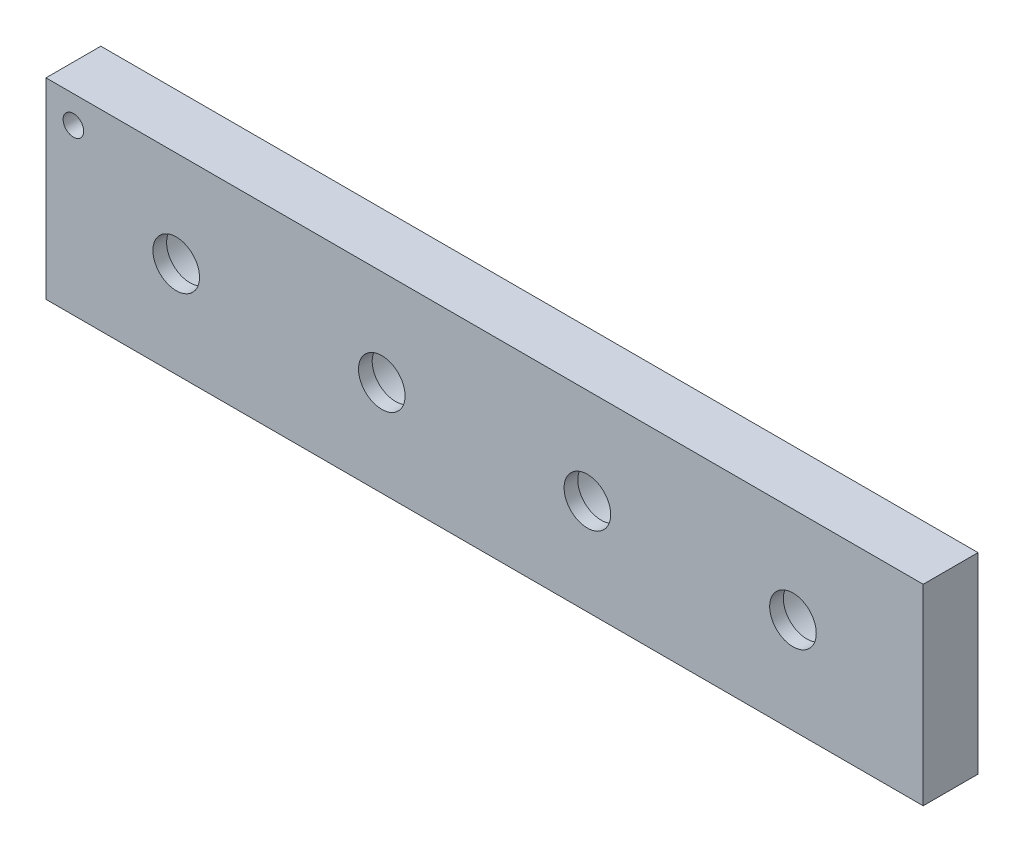
SolidWorks part; units mm, degrees
ref_plane "Front Plane" through (0, 0, 0) normal (0, 0, 1) x (1, 0, 0)
ref_plane "Top Plane" through (0, 0, 0) normal (0, 1, 0) x (1, 0, 0)
ref_plane "Right Plane" through (0, 0, 0) normal (1, 0, 0) x (0, 0, -1)
sketch "Coupon_bar_64x14x4_profile" plane through (0, 0, 0) normal (0, 0, 1) x (1, 0, 0)
  line L1 (-32, -7) -> (32, -7)
  line L2 (-32, -7) -> (-32, 7)
  line L3 (-32, 7) -> (32, 7)
  line L4 (32, -7) -> (32, 7)
  dimension "D1" = 64
  dimension "D2" = 14
  dimension "D3" = 32
  dimension "D4" = 7
extrude "Coupon_bar_64x14x4" add sketch "Coupon_bar_64x14x4_profile" along normal blind 4
sketch "Press_sockets_5p70_5p80_5p90_6p00_depth3_profile" plane through (0, 0, 0) normal (0, 0, 1) x (1, 0, 0)
  circle A0 centre (-22.5, 0) radius 2.85
  circle A1 centre (-7.5, 0) radius 2.9
  circle A2 centre (7.5, 0) radius 2.95
  circle A3 centre (22.5, 0) radius 3
  dimension "D1" = 5.7
  dimension "D2" = 5.8
  dimension "D3" = 5.9
  dimension "D4" = 6
  dimension "D5" = 7.5
  dimension "D6" = 22.5
  dimension "D7" = 7.5
  dimension "D8" = 22.5
extrude "Press_sockets_5p70_5p80_5p90_6p00_depth3" cut sketch "Press_sockets_5p70_5p80_5p90_6p00_depth3_profile" along normal blind 3
sketch "M3_centre_screw_clearance_profile" plane through (0, 0, 0) normal (0, 0, 1) x (1, 0, 0)
  circle A0 centre (-22.5, 0) radius 1.7
  circle A1 centre (-7.5, 0) radius 1.7
  circle A2 centre (7.5, 0) radius 1.7
  circle A3 centre (22.5, 0) radius 1.7
  dimension "D1" = 3.4
  dimension "D2" = 3.4
  dimension "D3" = 3.4
  dimension "D4" = 3.4
  dimension "D5" = 7.5
  dimension "D6" = 22.5
  dimension "D7" = 7.5
  dimension "D8" = 22.5
extrude "M3_centre_screw_clearance" cut sketch "M3_centre_screw_clearance_profile" along normal through all from offset 50
sketch "Orientation_mark_at_smallest_socket_profile" plane through (0, 0, 0) normal (0, 0, 1) x (1, 0, 0)
  circle A0 centre (-30, 5) radius 0.75
  dimension "D1" = 1.5
  dimension "D2" = 30
  dimension "D3" = 5
extrude "Orientation_mark_at_smallest_socket" cut sketch "Orientation_mark_at_smallest_socket_profile" along normal through all from offset 50
